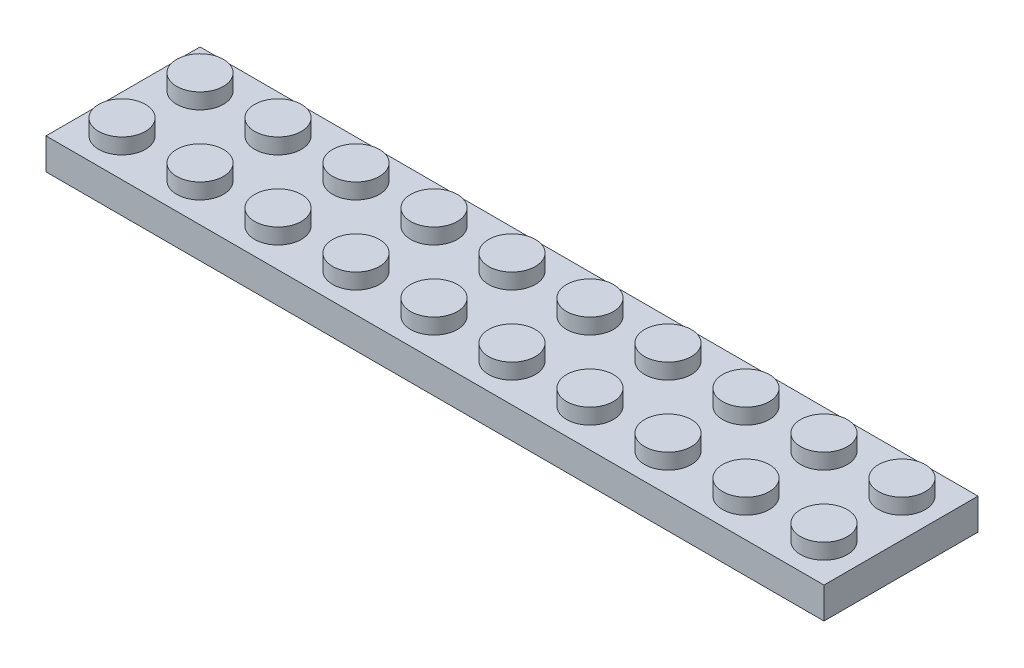
SolidWorks part; units mm, degrees
material "ABS"
ref_plane "Front Plane" through (0, 0, 0) normal (0, 0, 1) x (1, 0, 0)
ref_plane "Top Plane" through (0, 0, 0) normal (0, 1, 0) x (1, 0, 0)
ref_plane "Right Plane" through (0, 0, 0) normal (1, 0, 0) x (0, 0, -1)
sketch "Sketch1" plane through (0, 0, 0) normal (0, 0, 1) x (1, 0, 0)
  line L1 (0, 0) -> (79.8, 0)
  line L2 (0, 0) -> (0, 3.2)
  line L3 (0, 3.2) -> (79.8, 3.2)
  line L4 (79.8, 0) -> (79.8, 3.2)
  dimension "D1" = 3.2
  dimension "D2" = 79.8
extrude "Boss-Extrude1" add sketch "Sketch1" against normal blind 15.8
sketch "Sketch2" plane through (0, 3.2, 0) normal (0, 1, 0) x (1, 0, 0)
  line L0 (0, 15.8) -> (0, 0) construction
  line L1 (79.8, 0) -> (0, 0) construction
  circle A0 centre (3.9, 3.9) radius 2.4
  dimension "D1" = 4.8
  dimension "D2" = 3.9
  dimension "D3" = 3.9
extrude "Boss-Extrude2" add sketch "Sketch2" along normal blind 1.6 contours A0
pattern_linear "LPattern1" count 2 spacing 8 along (0, 0, -1) count 10 spacing 8 along (1, 0, 0) of "Boss-Extrude2"
shell "Shell1" thickness 1.2
sketch "Sketch3" plane through (0, 2, 0) normal (0, -1, 0) x (1, 0, 0)
  line L0 (0, -15.8) -> (0, 0) construction
  line L1 (0, -15.8) -> (79.8, -15.8) construction
  circle A0 centre (7.9, -7.9) radius 3.25
  circle A1 centre (7.9, -7.9) radius 2.4
  dimension "D1" = 4.8
  dimension "D2" = 6.5
  dimension "D3" = 7.9
  dimension "D4" = 7.9
extrude "Boss-Extrude3" add sketch "Sketch3" along normal offset from surface (1.8 mm away) 0.2 up to face at (39.9, 0, -7.9)
pattern_linear "LPattern2" count 9 spacing 8 along (1, 0, 0) of "Boss-Extrude3"
